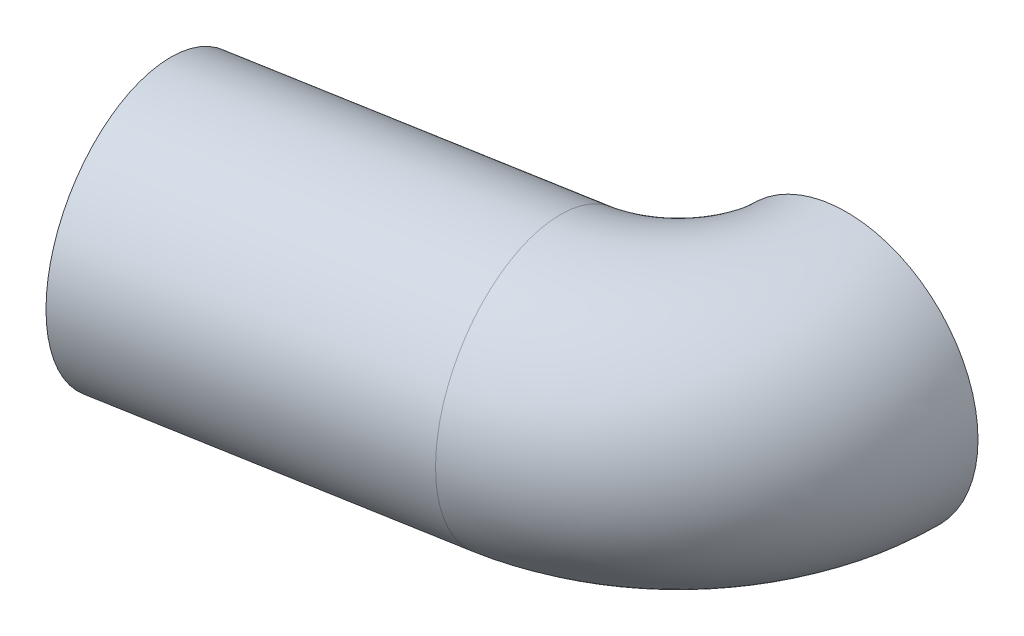
SolidWorks part; units mm, degrees
ref_plane "Plan de face" through (0, 0, 0) normal (0, 0, 1) x (1, 0, 0)
ref_plane "Plan de dessus" through (0, 0, 0) normal (0, 1, 0) x (1, 0, 0)
ref_plane "Plan de droite" through (0, 0, 0) normal (1, 0, 0) x (0, 0, -1)
sketch "Esquisse1" plane through (0, 0, 0) normal (0, 0, 1) x (1, 0, 0)
  line L0 (-32, 38.3387) -> (-32, -47.6969)
  circle A0 centre (0, 0) radius 25
  circle A1 centre (0, 0) radius 22.5
  dimension "D1" = 50
  dimension "D2" = 45
  dimension "D3" = 32
revolve "Révolution2" add sketch "Esquisse1" angle 80 about L0
sketch "Esquisse2" plane through (-31.0351, 0, 5.4723) normal (-0.9848, 0, 0.1736) x (0.1736, 0, 0.9848)
  circle A0 centre (26.4433, 0) radius 22.5
  circle A1 centre (26.4433, 0) radius 25
extrude "Boss.-Extru.1" add sketch "Esquisse2" along normal blind 64
